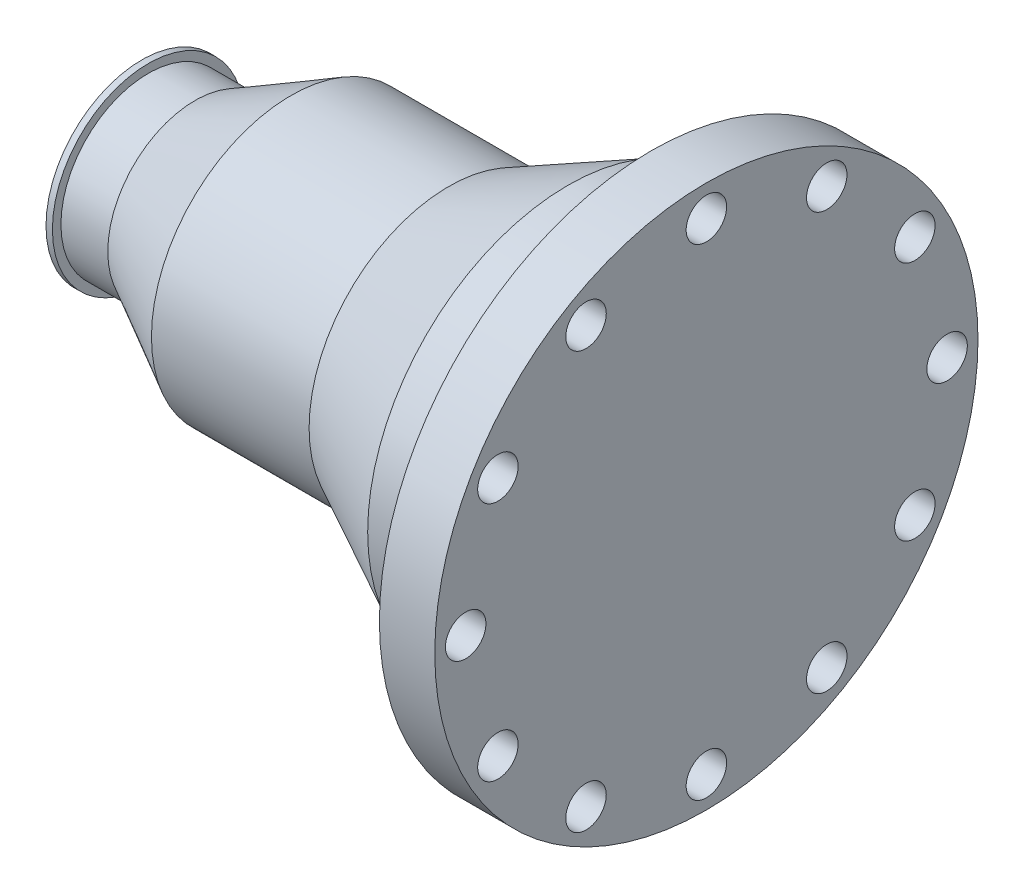
SolidWorks part; units mm, degrees
ref_plane "Спереди" through (0, 0, 0) normal (0, 0, 1) x (1, 0, 0)
ref_plane "Сверху" through (0, 0, 0) normal (0, 1, 0) x (1, 0, 0)
ref_plane "Справа" through (0, 0, 0) normal (1, 0, 0) x (0, 0, -1)
sketch "Эскиз1" plane through (0, 0, 0) normal (0, 0, 1) x (1, 0, 0)
  line L0 (0, 0) -> (265, 0)
  line L1 (0, 0) -> (0, 45)
  line L2 (0, 45) -> (3, 45)
  line L3 (3, 45) -> (3, 41)
  line L4 (3, 41) -> (25, 41)
  line L5 (25, 41) -> (70, 65.5)
  line L6 (70, 65.5) -> (144, 65.5)
  line L7 (144, 65.5) -> (200, 94)
  line L8 (200, 94) -> (220, 94)
  line L9 (220, 94) -> (220, 95)
  line L10 (220, 95) -> (239, 95)
  line L11 (239, 95) -> (239, 100)
  line L12 (239, 100) -> (239, 127.5)
  line L13 (239, 127.5) -> (265, 127.5)
  line L14 (265, 127.5) -> (265, 0)
revolve "Повернуть1" add sketch "Эскиз1" angle 360 about L0
sketch "Эскиз2" plane through (0, 0, 0) normal (0, 0, 1) x (1, 0, 0)
  line L0 (0, 0) -> (200, 0)
  line L1 (200, 94) -> (200, -94) construction
  line L2 (0, 0) -> (0, 31)
  line L3 (0, 45) -> (0, -45) construction
  line L4 (0, 31) -> (42, 31)
  line L5 (42, 31) -> (70, 38.5026)
  line L6 (70, 65.5) -> (70, -65.5) construction
  line L7 (90, 52.5) -> (142, 52.5)
  line L8 (143.5, 52.5) -> (146.6699, 52.5)
  line L9 (147.6699, 55) -> (200, 55)
  line L10 (200, 55) -> (200, 0)
  arc A0 (70, 38.5026) -> (90, 52.5) centre (107.8022, 5.7765) cw
  arc A1 (142, 52.5) -> (143.5, 52.5) centre (142.75, 49.8032) cw
  arc A2 (146.6699, 52.5) -> (147.6699, 55) centre (147.5934, 53.5806) cw
revolve "Вырез-Повернуть1" cut sketch "Эскиз2" angle 360 about L0
sketch "Эскиз3" plane through (0, 0, 0) normal (1, 0, 0) x (0, 0, -1)
  circle A0 centre (0, 113) radius 9.5
extrude "Вырез-Вытянуть1" cut sketch "Эскиз3" along normal through all
sketch "Эскиз4" plane through (0, 0, 0) normal (1, 0, 0) x (0, 0, -1)
  circle A0 centre (-56.5, 97.8609) radius 9.5
extrude "Вырез-Вытянуть2" cut sketch "Эскиз4" along normal through all
sketch "Эскиз5" plane through (0, 0, 0) normal (1, 0, 0) x (0, 0, -1)
  circle A0 centre (-97.8609, 56.5) radius 9.5
extrude "Вырез-Вытянуть3" cut sketch "Эскиз5" along normal through all
sketch "Эскиз6" plane through (0, 0, 0) normal (1, 0, 0) x (0, 0, -1)
  circle A0 centre (-113, 0) radius 9.5
extrude "Вырез-Вытянуть4" cut sketch "Эскиз6" along normal through all
sketch "Эскиз7" plane through (0, 0, 0) normal (1, 0, 0) x (0, 0, -1)
  circle A0 centre (-97.8609, -56.5) radius 9.5
extrude "Вырез-Вытянуть5" cut sketch "Эскиз7" along normal through all
sketch "Эскиз8" plane through (0, 0, 0) normal (1, 0, 0) x (0, 0, -1)
  circle A0 centre (-56.5, -97.8609) radius 9.5
extrude "Вырез-Вытянуть6" cut sketch "Эскиз8" along normal through all
sketch "Эскиз9" plane through (0, 0, 0) normal (1, 0, 0) x (0, 0, -1)
  circle A0 centre (0, -113) radius 9.5
extrude "Вырез-Вытянуть7" cut sketch "Эскиз9" along normal through all
sketch "Эскиз10" plane through (0, 0, 0) normal (1, 0, 0) x (0, 0, -1)
  circle A0 centre (56.5, -97.8609) radius 9.5
extrude "Вырез-Вытянуть8" cut sketch "Эскиз10" along normal through all
sketch "Эскиз11" plane through (0, 0, 0) normal (1, 0, 0) x (0, 0, -1)
  circle A0 centre (97.8609, -56.5) radius 9.5
extrude "Вырез-Вытянуть9" cut sketch "Эскиз11" along normal through all
sketch "Эскиз12" plane through (0, 0, 0) normal (1, 0, 0) x (0, 0, -1)
  circle A0 centre (113, 0) radius 9.5
extrude "Вырез-Вытянуть10" cut sketch "Эскиз12" along normal through all
sketch "Эскиз13" plane through (0, 0, 0) normal (1, 0, 0) x (0, 0, -1)
  circle A0 centre (97.8609, 56.5) radius 9.5
extrude "Вырез-Вытянуть11" cut sketch "Эскиз13" along normal through all
sketch "Эскиз14" plane through (0, 0, 0) normal (1, 0, 0) x (0, 0, -1)
  circle A0 centre (56.5, 97.8609) radius 9.5
extrude "Вырез-Вытянуть12" cut sketch "Эскиз14" along normal through all
